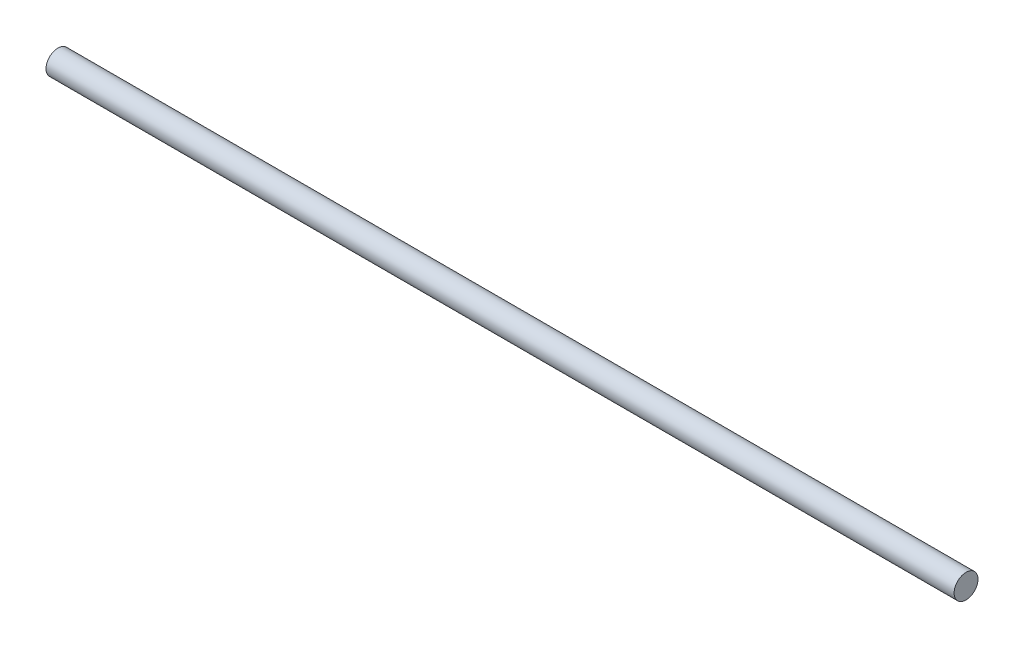
SolidWorks part; units mm, degrees
ref_plane "Front Plane" through (0, 0, 0) normal (0, 0, 1) x (1, 0, 0)
ref_plane "Top Plane" through (0, 0, 0) normal (0, 1, 0) x (1, 0, 0)
ref_plane "Right Plane" through (0, 0, 0) normal (1, 0, 0) x (0, 0, -1)
sketch "Sketch1" plane through (0, 0, 0) normal (0, 0, 1) x (1, 0, 0)
  line L1 (-89.5599, 15.1372) -> (130.4401, 15.1372)
  line L2 (-89.5599, 15.1372) -> (-89.5599, 12.2372)
  line L3 (-89.5599, 12.2372) -> (130.4401, 12.2372)
  line L4 (130.4401, 15.1372) -> (130.4401, 12.2372)
  dimension "D1" = 220
  dimension "D2" = 2.9
revolve "Revolve1" add sketch "Sketch1" angle 360 about L1
